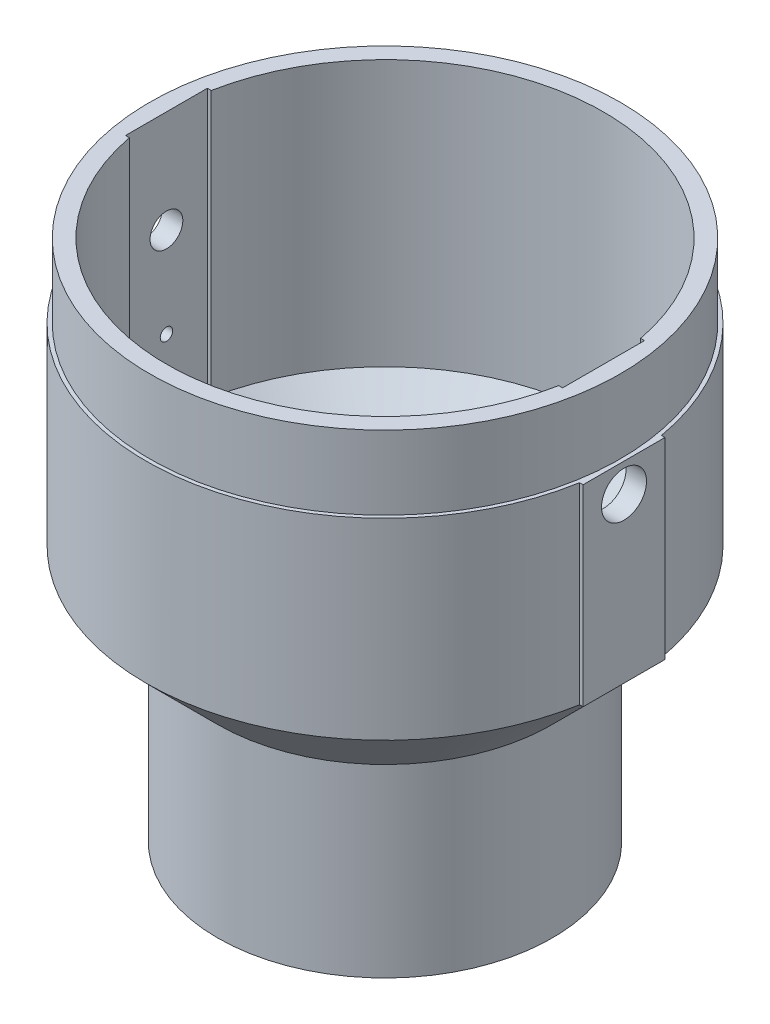
SolidWorks part; units mm, degrees
ref_plane "Front Plane" through (0, 0, 0) normal (0, 0, 1) x (1, 0, 0)
ref_plane "Top Plane" through (0, 0, 0) normal (0, 1, 0) x (1, 0, 0)
ref_plane "Right Plane" through (0, 0, 0) normal (1, 0, 0) x (0, 0, -1)
sketch "Sketch1" plane through (0, 0, 0) normal (0, 0, 1) x (1, 0, 0)
  line L0 (58.41, -65) -> (40.91, -82.5)
  line L2 (58.41, 0) -> (58.41, -65)
  line L4 (40.91, -82.5) -> (40.91, -127.6795)
  line L14 (35.91, -127.6795) -> (40.91, -127.6795)
  line L15 (53.41, -65) -> (53.41, 0)
  line L16 (53.41, -65) -> (35.91, -82.5)
  line L17 (35.91, -82.5) -> (35.91, -127.6795)
  line L20 (0, 0) -> (58.41, 0) construction
  line L21 (53.41, 0) -> (58.41, 0)
  line L22 (0, 0) -> (0, -70.7807) construction
  dimension "D1" = 58.41
  dimension "D2" = 45.1795
  dimension "D3" = 135
  dimension "D4" = 5
  dimension "D5" = 65
  dimension "D6" = 17.5
revolve "Revolve1" add sketch "Sketch1" angle 360 about L22
ref_plane "Plane3" through (0, 0, -65) normal (0, 0, 1) x (1, 0, 0)
ref_plane "Plane4" through (-58.41, 0, 0) normal (-1, 0, 0) x (0, 0, 1)
sketch "Sketch14" plane through (0, 0, 0) normal (0, 0, 1) x (1, 0, 0)
  line L1 (-58.41, 0) -> (-58.41, -65) construction
  line L2 (-58.41, 0) -> (-57.5, 0)
  line L3 (-57.5, 0) -> (-57.5, -18)
  line L4 (-57.5, -18) -> (-58.41, -18)
  line L5 (-58.41, 0) -> (-58.41, -18)
  point P0 (-58.41, -0.7488)
  point P7 (-56.5269, -6.4224)
  dimension "D1" = 18
  dimension "D2" = 57.5
revolve "Cut-Revolve5" cut sketch "Sketch14" angle 360 about axis through (0, 0, 0) along (0, 1, 0)
sketch "Sketch8" plane through (-58.41, 0, 0) normal (-1, 0, 0) x (0, 0, 1)
  line L1 (-10, -18) -> (10, -18)
  line L2 (-10, -18) -> (-10, -65)
  line L3 (-10, -65) -> (10, -65)
  line L4 (10, -18) -> (10, -65)
  line L5 (58.41, -65) -> (-58.41, -65) construction
  line L6 (58.41, -18) -> (-58.41, -18) construction
  line L7 (0, -18) -> (0, 0) construction
  dimension "D1" = 20
extrude "Boss-Extrude1" add sketch "Sketch8" against normal up to surface (0.8624 mm away)
ref_plane "Plane5" through (-53.41, 0, 0) normal (1, 0, 0) x (0, 0, -1)
sketch "Sketch10" plane through (-53.41, 0, 0) normal (1, 0, 0) x (0, 0, -1)
  line L1 (10, 0) -> (-10, 0)
  line L2 (10, 0) -> (10, -65)
  line L3 (10, -65) -> (-10, -65)
  line L4 (-10, 0) -> (-10, -65)
extrude "Cut-Extrude4" cut sketch "Sketch10" along normal up to surface (0.9445 mm away)
pattern_circular "CirPattern1" count 2 every 180 about axis through (0, 0, 0) along (0, 1, 0) of "Boss-Extrude1", "Cut-Extrude4"
sketch "Sketch11" plane through (58.41, 0, 0) normal (1, 0, 0) x (0, 0, -1)
  circle A0 centre (0, -25) radius 5.5
  dimension "D1" = 11
  dimension "D2" = 25
extrude "Cut-Extrude5" cut sketch "Sketch11" against normal up to surface (5 mm away) up to face at (53.41, -39, 0)
sketch "Sketch12" plane through (-58.41, 0, 0) normal (-1, 0, 0) x (0, 0, 1)
  circle A0 centre (0, -25) radius 4
  circle A1 centre (0, -47.0538) radius 1.515
  circle A2 centre (0, -57.0538) radius 1.515
  circle A3 centre (0, -25) radius 5.5 construction
  dimension "D1" = 8
  dimension "D2" = 3.03
  dimension "D3" = 22.0538
  dimension "D4" = 32.0538
extrude "Cut-Extrude6" cut sketch "Sketch12" against normal up to surface (5 mm away) up to face at (-53.41, -39, 0)
